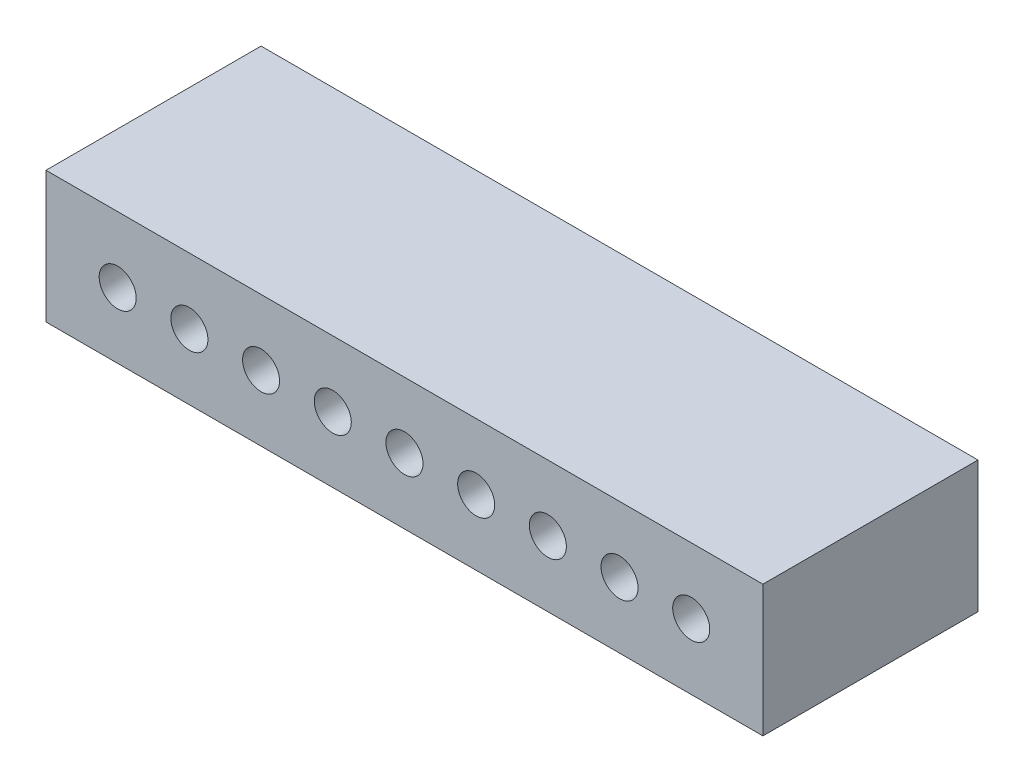
SolidWorks part; units mm, degrees
ref_plane "前视基准面" through (0, 0, 0) normal (0, 0, 1) x (1, 0, 0)
ref_plane "上视基准面" through (0, 0, 0) normal (0, 1, 0) x (1, 0, 0)
ref_plane "右视基准面" through (0, 0, 0) normal (1, 0, 0) x (0, 0, -1)
sketch "草图1" plane through (0, 0, 0) normal (0, 1, 0) x (1, 0, 0)
  line L1 (-30, 9) -> (30, 9)
  line L2 (-30, 9) -> (-30, -9)
  line L3 (-30, -9) -> (30, -9)
  line L4 (30, 9) -> (30, -9)
  line L5 (-30, 9) -> (30, -9) construction
  line L6 (-30, -9) -> (30, 9) construction
  point P0 (0, 0)
  dimension "D1" = 18
  dimension "D2" = 60
extrude "凸台-拉伸1" add sketch "草图1" along normal blind 11
sketch "草图2" plane through (0, 0, 9) normal (0, 0, 1) x (1, 0, 0)
  line L0 (-30, 5.5) -> (49.2758, 5.5) construction
  line L1 (-30, 11) -> (-30, 0) construction
  circle A1 centre (-24, 5.5) radius 1.55
  circle A2 centre (-18, 5.5) radius 1.55
  circle A3 centre (-12, 5.5) radius 1.55
  circle A4 centre (-6, 5.5) radius 1.55
  circle A5 centre (0, 5.5) radius 1.55
  circle A6 centre (6, 5.5) radius 1.55
  circle A7 centre (12, 5.5) radius 1.55
  circle A8 centre (18, 5.5) radius 1.55
  circle A9 centre (24, 5.5) radius 1.55
extrude "切除-拉伸2" cut sketch "草图2" against normal through all
